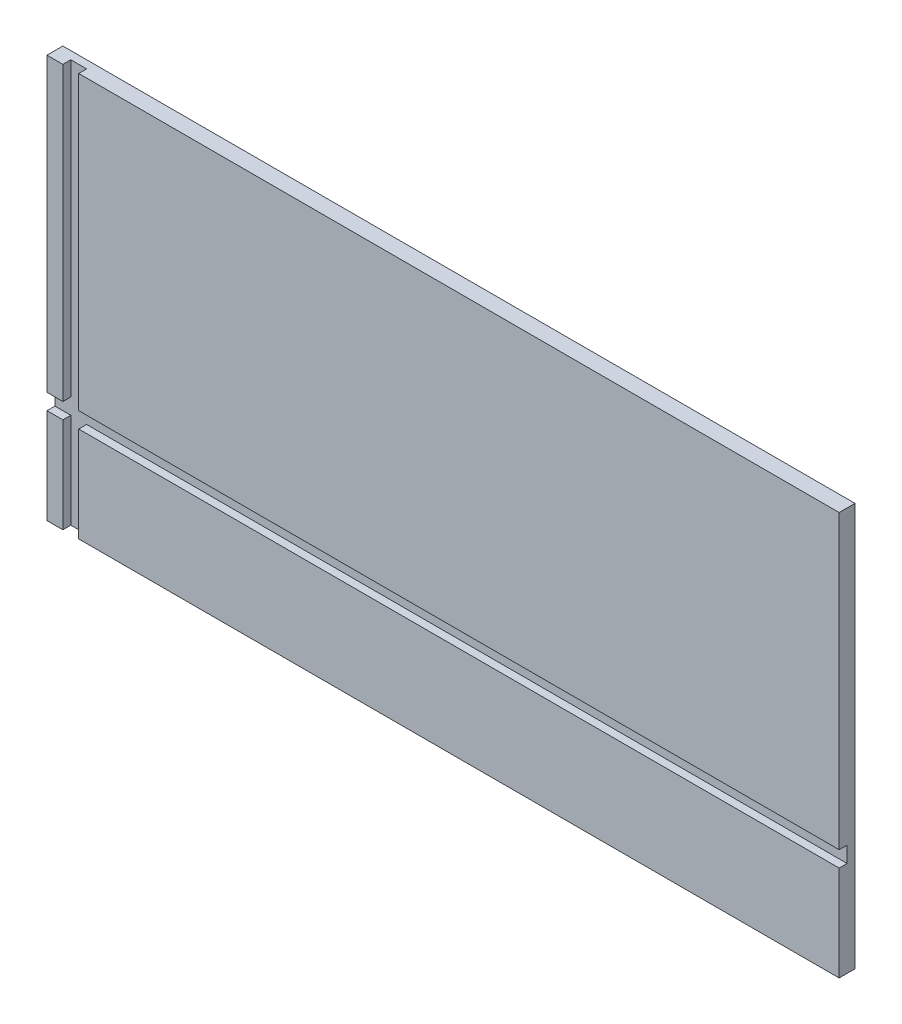
SolidWorks part; units mm, degrees
ref_plane "Front Plane" through (0, 0, 0) normal (0, 0, 1) x (1, 0, 0)
ref_plane "Top Plane" through (0, 0, 0) normal (0, 1, 0) x (1, 0, 0)
ref_plane "Right Plane" through (0, 0, 0) normal (1, 0, 0) x (0, 0, -1)
sketch "Sketch1" plane through (0, 0, 0) normal (0, 0, 1) x (1, 0, 0)
  line L0 (89.265, 0) -> (148.955, 0)
  line L1 (89.265, 0) -> (0, 0)
  line L2 (0, 0) -> (0, 80.645)
  line L3 (0, 80.645) -> (148.955, 80.645)
  line L4 (148.955, 80.645) -> (148.955, 0)
extrude "Boss-Extrude1" add sketch "Sketch1" along normal blind 3.175
sketch "Sketch2" plane through (148.955, 0, 0) normal (1, 0, 0) x (0, 0, -1)
  line L1 (-3.175, 0) -> (-3.175, 80.645) construction
  line L2 (-3.175, 19.05) -> (-3.175, 22.225)
  line L3 (-3.175, 22.225) -> (-1.5875, 22.225)
  line L4 (-1.5875, 22.225) -> (-1.5875, 19.05)
  line L5 (-1.5875, 19.05) -> (-3.175, 19.05)
extrude "Cut-Extrude1" cut sketch "Sketch2" against normal through all
sketch "Sketch4" plane through (0, 0, 0) normal (-1, 0, 0) x (0, 0, 1)
  line L0 (3.175, 19.05) -> (3.175, 0)
  line L1 (0, 80.645) -> (3.175, 80.645)
  line L2 (0, 80.645) -> (0, 0)
  line L3 (0, 0) -> (3.175, 0)
  line L4 (3.175, 80.645) -> (3.175, 22.225)
  line L5 (1.5875, 19.05) -> (3.175, 19.05)
  line L6 (1.5875, 19.05) -> (1.5875, 22.225)
  line L7 (1.5875, 22.225) -> (3.175, 22.225)
extrude "Boss-Extrude2" add sketch "Sketch4" along normal blind 9.525
sketch "Sketch5" plane through (0, 0, 3.175) normal (0, 0, 1) x (1, 0, 0)
  line L1 (148.955, 80.645) -> (-9.525, 80.645) construction
  line L2 (-6.35, 80.645) -> (-6.35, 0)
  line L3 (-9.525, 0) -> (148.955, 0) construction
  line L4 (-6.35, 0) -> (-3.175, 0)
  line L5 (-3.175, 0) -> (-3.175, 80.645)
  line L6 (-3.175, 80.645) -> (-6.35, 80.645)
extrude "Cut-Extrude2" cut sketch "Sketch5" against normal blind 1.5875
